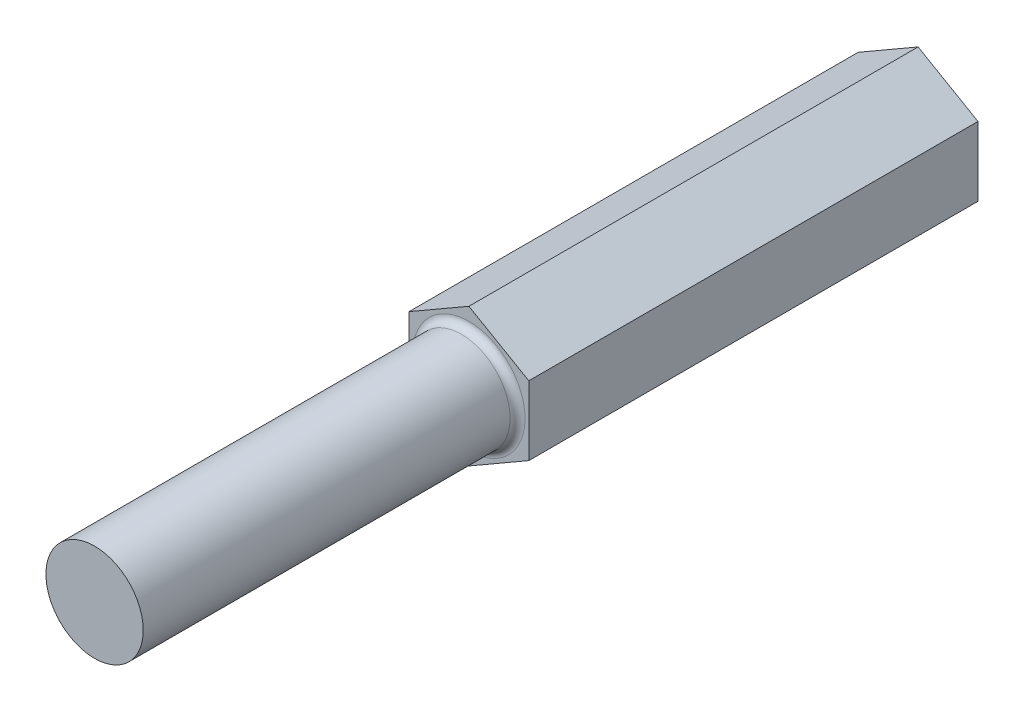
SolidWorks part; units mm, degrees
material "Plastique personnalisé"
ref_plane "Plan de face" through (0, 0, 0) normal (0, 0, 1) x (1, 0, 0)
ref_plane "Plan de dessus" through (0, 0, 0) normal (0, 1, 0) x (1, 0, 0)
ref_plane "Plan de droite" through (0, 0, 0) normal (1, 0, 0) x (0, 0, -1)
sketch "Esquisse1" plane through (0, 0, 0) normal (0, 0, 1) x (1, 0, 0)
  line L1 (-4, 2.3094) -> (-4, -2.3094)
  line L2 (-4, -2.3094) -> (0, -4.6188)
  line L3 (0, -4.6188) -> (4, -2.3094)
  line L4 (4, -2.3094) -> (4, 2.3094)
  line L5 (4, 2.3094) -> (0, 4.6188)
  line L6 (0, 4.6188) -> (-4, 2.3094)
  circle A0 centre (0, 0) radius 4 construction
  dimension "D1" = 8
extrude "Boss.-Extru.1" add sketch "Esquisse1" along normal blind 30
sketch "Esquisse2" plane through (0, 0, 30) normal (0, 0, 1) x (1, 0, 0)
  circle A0 centre (0, 0) radius 3.25
  dimension "D1" = 6.5
extrude "Boss.-Extru.2" add sketch "Esquisse2" along normal blind 25
fillet "Congé1" radius 0.5 1 edges at (3.25, 0, 30)
